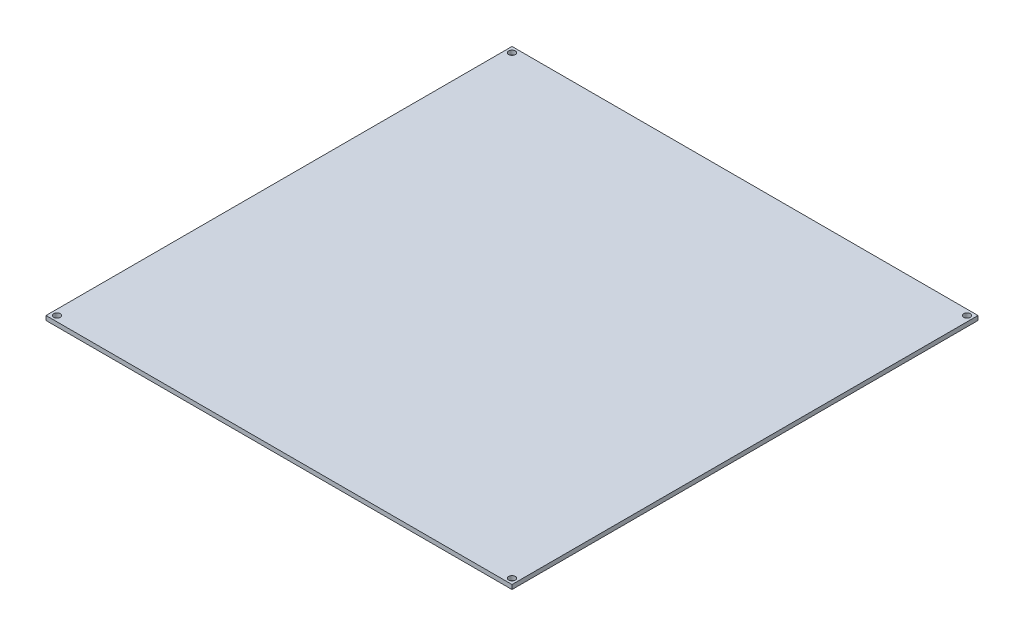
SolidWorks part; units mm, degrees
material "3.1655 (EN AW-2011)"
ref_plane "Přední rovina" through (0, 0, 0) normal (0, 0, 1) x (1, 0, 0)
ref_plane "Horní rovina" through (0, 0, 0) normal (0, 1, 0) x (1, 0, 0)
ref_plane "Pravá rovina" through (0, 0, 0) normal (1, 0, 0) x (0, 0, -1)
sketch "Skica1" plane through (0, 0, 0) normal (0, 1, 0) x (1, 0, 0)
  line L0 (0, -107) -> (104.5, -107) construction
  line L1 (107, -107) -> (-107, -107)
  line L2 (107, -107) -> (107, 107)
  line L3 (107, 107) -> (-107, 107)
  line L4 (-107, -107) -> (-107, 107)
  line L5 (107, -107) -> (-107, 107) construction
  line L6 (107, 107) -> (-107, -107) construction
  line L7 (104.5, -107) -> (104.5, -104.5) construction
  line L8 (-107, -107) -> (-104.5, -107) construction
  line L9 (-104.5, -107) -> (-104.5, -104.5) construction
  line L10 (-107, 107) -> (-104.5, 107) construction
  line L11 (-104.5, 107) -> (-104.5, 104.5) construction
  line L12 (107, 107) -> (104.5, 107) construction
  line L13 (104.5, 107) -> (104.5, 104.5) construction
  circle A0 centre (104.5, 104.5) radius 1.5
  circle A1 centre (-104.5, 104.5) radius 1.5
  circle A2 centre (-104.5, -104.5) radius 1.5
  circle A3 centre (104.5, -104.5) radius 1.5
  point P0 (0, 0)
  dimension "D1" = 214
  dimension "D2" = 214
  dimension "D3" = 104.5
  dimension "D4" = 2.5
extrude "Přidat vysunutím1" add sketch "Skica1" along normal blind 2
